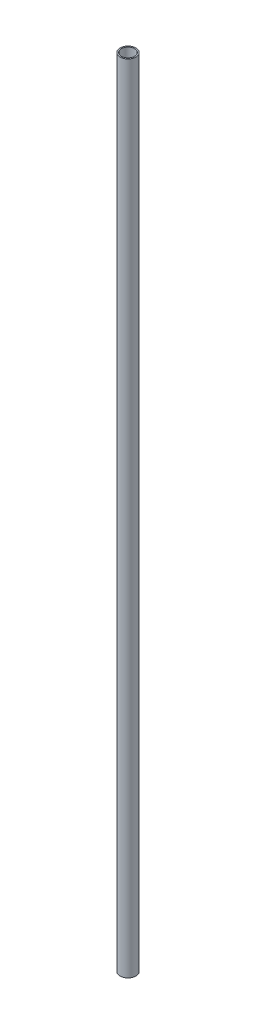
SolidWorks part; units mm, degrees
material "Hexcel AS4C (3000 Filaments)"
ref_plane "Front Plane" through (0, 0, 0) normal (0, 0, 1) x (1, 0, 0)
ref_plane "Top Plane" through (0, 0, 0) normal (0, 1, 0) x (1, 0, 0)
ref_plane "Right Plane" through (0, 0, 0) normal (1, 0, 0) x (0, 0, -1)
sketch "Sketch1" plane through (0, 0, 0) normal (0, 1, 0) x (1, 0, 0)
  circle A0 centre (0, 0) radius 5
  circle A1 centre (0, 0) radius 6
  dimension "D1" = 12
  dimension "D2" = 10
extrude "Boss-Extrude1" add sketch "Sketch1" along normal blind 600
